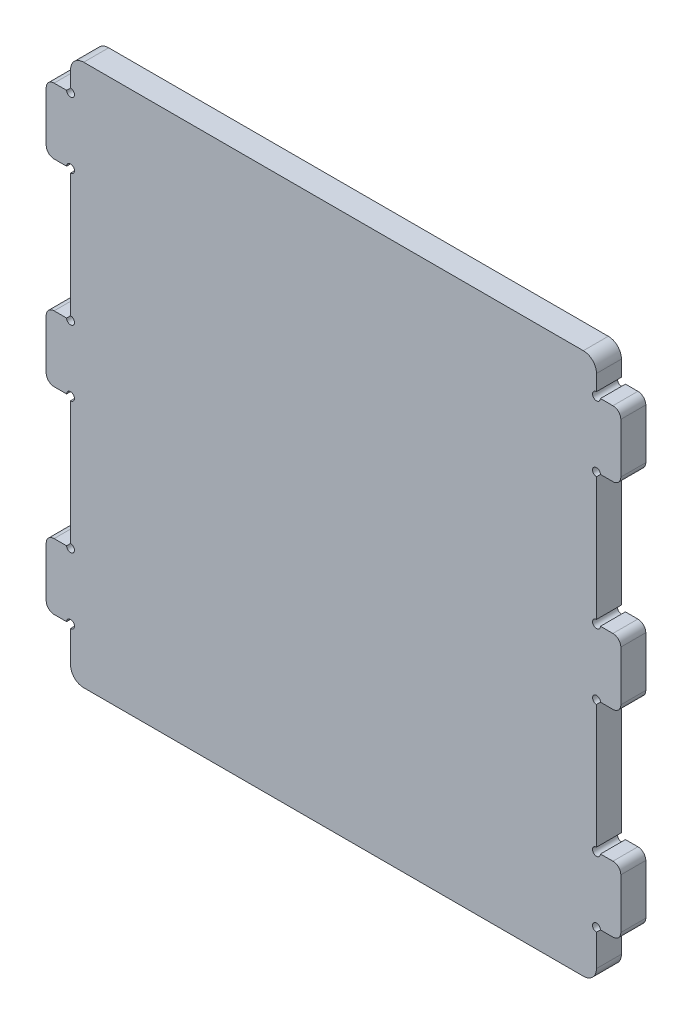
SolidWorks part; units mm, degrees
ref_plane "Front Plane" through (0, 0, 0) normal (0, 0, 1) x (1, 0, 0)
ref_plane "Top Plane" through (0, 0, 0) normal (0, 1, 0) x (1, 0, 0)
ref_plane "Right Plane" through (0, 0, 0) normal (1, 0, 0) x (0, 0, -1)
sketch "Sketch1" plane through (0, 0, 0) normal (0, 0, 1) x (1, 0, 0)
  line L0 (-212.5, 31) -> (-200, 31)
  line L1 (-190, 206) -> (190, 206)
  line L2 (-200, 196) -> (-200, -196)
  line L3 (-190, -206) -> (190, -206)
  line L4 (200, 196) -> (200, -196)
  line L5 (-200, 206) -> (200, -206) construction
  line L6 (-200, -206) -> (200, 206) construction
  line L7 (-212.5, -119) -> (-200, -119)
  line L8 (-218.5, -125) -> (-218.5, -163)
  line L9 (-212.5, -169) -> (-200, -169)
  line L10 (-218.5, 25) -> (-218.5, -13)
  line L11 (-212.5, -19) -> (-200, -19)
  line L12 (-212.5, 181) -> (-200, 181)
  line L13 (-218.5, 175) -> (-218.5, 137)
  line L14 (-212.5, 131) -> (-200, 131)
  line L15 (0, 81.9141) -> (0, -62.7075)
  line L16 (212.5, 131) -> (200, 131)
  line L17 (218.5, 175) -> (218.5, 137)
  line L18 (212.5, 181) -> (200, 181)
  line L19 (212.5, -19) -> (200, -19)
  line L20 (218.5, 25) -> (218.5, -13)
  line L21 (212.5, -169) -> (200, -169)
  line L22 (218.5, -125) -> (218.5, -163)
  line L23 (212.5, -119) -> (200, -119)
  line L24 (212.5, 31) -> (200, 31)
  arc A0 (-218.5, -163) -> (-212.5, -169) centre (-212.5, -163) ccw
  arc A1 (-212.5, -119) -> (-218.5, -125) centre (-212.5, -125) ccw
  arc A2 (-218.5, -13) -> (-212.5, -19) centre (-212.5, -13) ccw
  arc A3 (-212.5, 31) -> (-218.5, 25) centre (-212.5, 25) ccw
  arc A4 (-218.5, 137) -> (-212.5, 131) centre (-212.5, 137) ccw
  arc A5 (-212.5, 181) -> (-218.5, 175) centre (-212.5, 175) ccw
  arc A6 (212.5, 181) -> (218.5, 175) centre (212.5, 175) cw
  arc A7 (218.5, 137) -> (212.5, 131) centre (212.5, 137) cw
  arc A8 (212.5, 31) -> (218.5, 25) centre (212.5, 25) cw
  arc A9 (218.5, -13) -> (212.5, -19) centre (212.5, -13) cw
  arc A10 (212.5, -119) -> (218.5, -125) centre (212.5, -125) cw
  arc A11 (218.5, -163) -> (212.5, -169) centre (212.5, -163) cw
  arc A12 (-200, -196) -> (-190, -206) centre (-190, -196) ccw
  arc A13 (190, -206) -> (200, -196) centre (190, -196) ccw
  arc A14 (190, 206) -> (200, 196) centre (190, 196) cw
  arc A15 (-190, 206) -> (-200, 196) centre (-190, 196) ccw
  circle A16 centre (200, -169) radius 3
  circle A17 centre (200, -119) radius 3
  circle A18 centre (200, 31) radius 3
  circle A19 centre (200, -19) radius 3
  circle A20 centre (200, 181) radius 3
  circle A21 centre (200, 131) radius 3
  circle A22 centre (-200, -19) radius 3
  circle A23 centre (-200, 31) radius 3
  circle A24 centre (-200, 131) radius 3
  circle A25 centre (-200, 181) radius 3
  circle A26 centre (-200, -169) radius 3
  circle A27 centre (-200, -119) radius 3
  point P0 (0, 0)
  point P6 (-200, -144)
  point P7 (-200, -144)
  point P14 (-218.5, -169)
  point P17 (-218.5, -119)
  point P20 (-200, 6)
  point P21 (-200, 6)
  point P30 (-200, 156)
  point P31 (-200, 156)
  point P64 (200, 156)
  point P65 (200, 6)
  point P66 (218.5, -119)
  point P67 (218.5, -169)
  point P68 (200, -144)
  dimension "D6" = 6
  dimension "D8" = 10
  dimension "D9" = 6
  dimension "D10" = 6
  dimension "D1" = 412
  dimension "D2" = 400
  dimension "D3" = 62
  dimension "D4" = 50
  dimension "D5" = 18.5
  dimension "D7" = 3
  dimension "D11" = 3
extrude "Boss-Extrude1" add sketch "Sketch1" along normal blind 19
